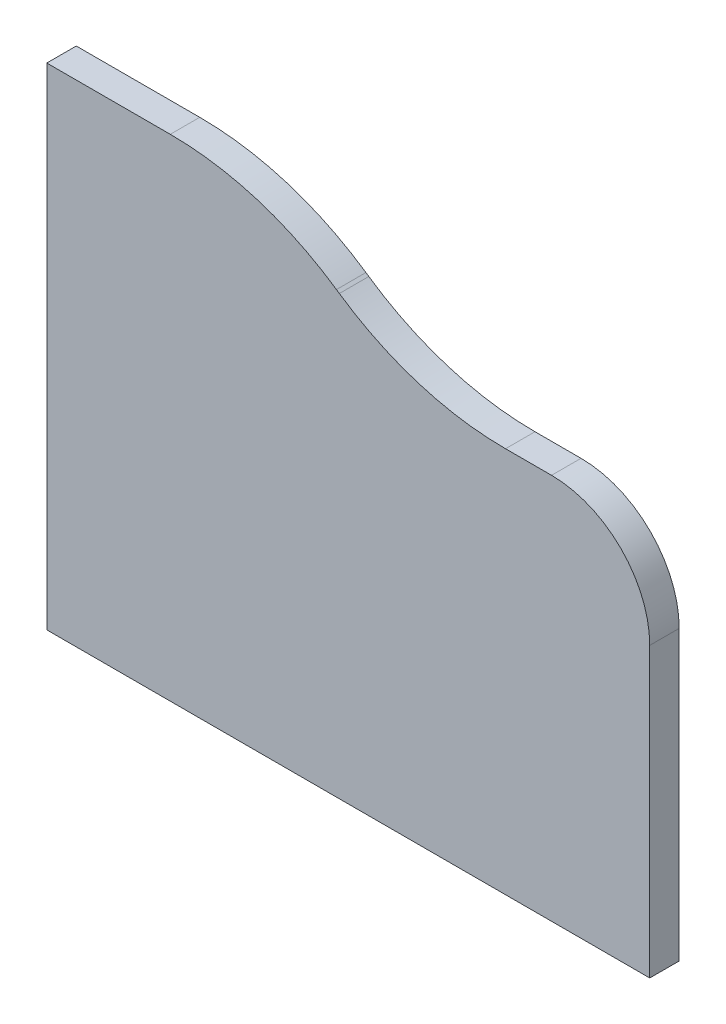
SolidWorks part; units mm, degrees
ref_plane "Alzado" through (0, 0, 0) normal (0, 0, 1) x (1, 0, 0)
ref_plane "Planta" through (0, 0, 0) normal (0, 1, 0) x (1, 0, 0)
ref_plane "Vista lateral" through (0, 0, 0) normal (1, 0, 0) x (0, 0, -1)
sketch "Croquis1" plane through (0, 0, 0) normal (0, 0, 1) x (1, 0, 0)
  line L1 (-61.6878, -25) -> (61.1278, -25)
  line L2 (-61.6878, -25) -> (-61.6878, 75)
  line L5 (61.1278, -25) -> (61.1278, 33.6775)
  line L9 (-61.6878, 75) -> (-36.5341, 75)
  line L10 (-2.6854, 64.5405) -> (-2.0948, 64.137)
  line L11 (31.754, 53.6775) -> (41.1278, 53.6775)
  arc A3 (-2.0948, 64.137) -> (31.754, 53.6775) centre (31.754, 113.6775) ccw
  arc A4 (-36.5341, 75) -> (-2.6854, 64.5405) centre (-36.5341, 15) cw
  arc A5 (61.1278, 33.6775) -> (41.1278, 53.6775) centre (41.1278, 33.6775) ccw
  dimension "D2" = 60
  dimension "D3" = 20
  dimension "D1" = 122.8156
  dimension "D4" = 100
extrude "Saliente-Extruir1" add sketch "Croquis1" along normal blind 6
sketch "Croquis2" plane through (0, 0, 0) normal (0, 1, 0) x (1, 0, 0)
  arc A0 (-61.4078, 0) -> (58.5922, 0) centre (-1.4078, -153.7043) cw
sketch "Croquis3" plane through (0, -25, 0) normal (0, -1, 0) x (1, 0, 0)
  arc A0 (-61.4078, 0) -> (58.5922, 0) centre (-1.4078, 153.7043) ccw
